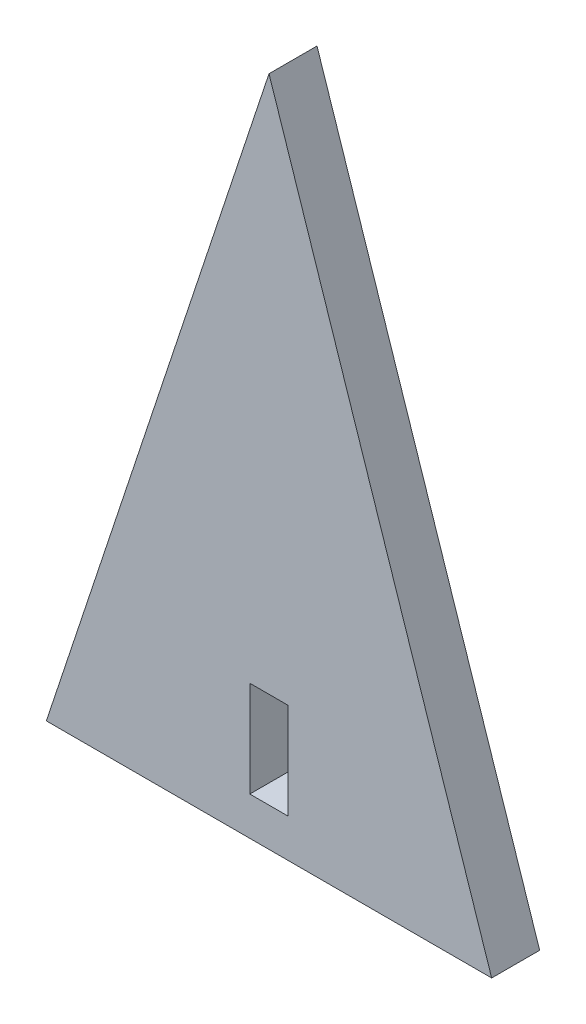
SolidWorks part; units mm, degrees
ref_plane "Front Plane" through (0, 0, 0) normal (0, 0, 1) x (1, 0, 0)
ref_plane "Top Plane" through (0, 0, 0) normal (0, 1, 0) x (1, 0, 0)
ref_plane "Right Plane" through (0, 0, 0) normal (1, 0, 0) x (0, 0, -1)
sketch "Sketch2" plane through (0, 0, 0) normal (0, 0, 1) x (1, 0, 0)
  line L0 (-16.0846, -40.3688) -> (-1.3526, 4.0812)
  line L1 (-16.0846, -40.3688) -> (13.3794, -40.3688)
  line L5 (-16.0846, -40.3688) -> (8.9252, 22.4002) construction
  line L6 (-16.0846, 48.5312) -> (13.3794, -40.3688) construction
  line L7 (-1.3526, 4.0812) -> (13.3794, -40.3688)
  line L8 (-1.3526, -40.3688) -> (-1.3526, -37.8288) construction
  line L10 (-2.6226, -37.8288) -> (-0.0826, -37.8288)
  line L11 (-2.6226, -37.8288) -> (-2.6226, -31.4788)
  line L12 (-2.6226, -31.4788) -> (-0.0826, -31.4788)
  line L13 (-0.0826, -37.8288) -> (-0.0826, -31.4788)
  point P0 (0, 0)
  point P13 (-1.3526, -37.8288)
  dimension "D1" = 29.464
  dimension "D2" = 44.45
  dimension "D3" = 2.54
  dimension "D4" = 41.91
  dimension "D5" = 2.54
  dimension "D6" = 6.35
  dimension "D7" = 5.5344
  dimension "D8" = 2.54
extrude "Boss-Extrude1" add sketch "Sketch2" along normal blind 3.175
